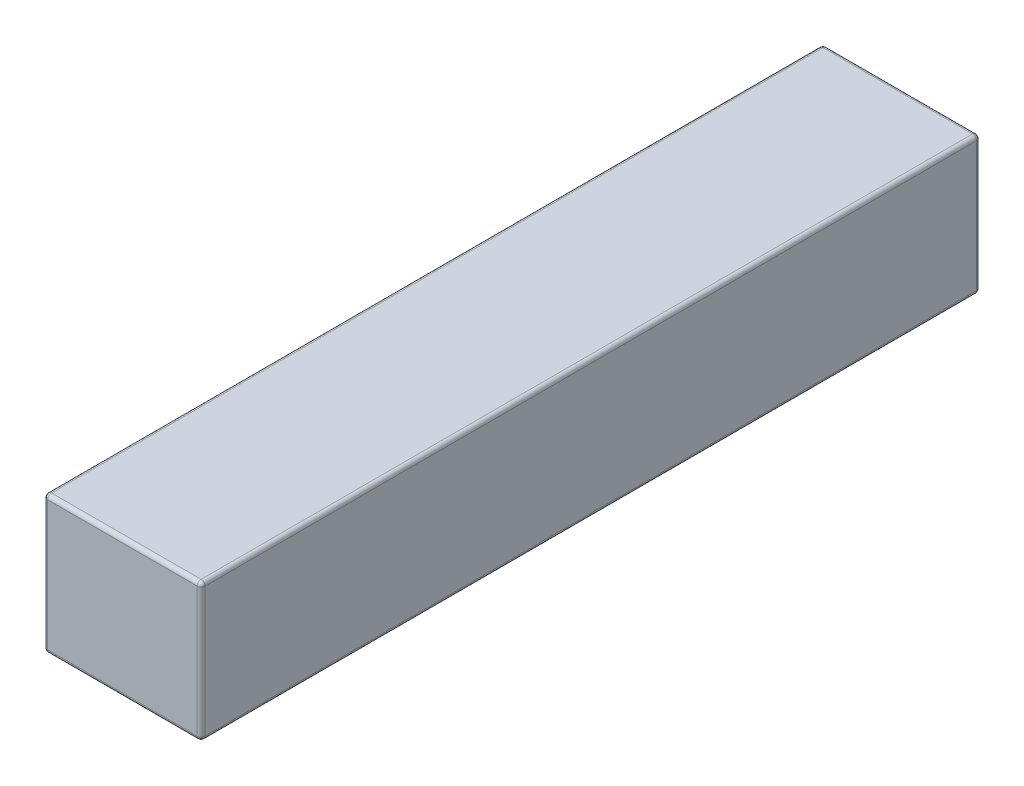
SolidWorks part; units mm, degrees
ref_plane "Front Plane" through (0, 0, 0) normal (0, 0, 1) x (1, 0, 0)
ref_plane "Top Plane" through (0, 0, 0) normal (0, 1, 0) x (1, 0, 0)
ref_plane "Right Plane" through (0, 0, 0) normal (1, 0, 0) x (0, 0, -1)
sketch "Sketch1" plane through (0, 0, 0) normal (0, 0, 1) x (1, 0, 0)
  line L1 (200, -175) -> (-200, -175)
  line L2 (200, -175) -> (200, 175)
  line L3 (200, 175) -> (-200, 175)
  line L4 (-200, -175) -> (-200, 175)
  line L5 (200, -175) -> (-200, 175) construction
  line L6 (200, 175) -> (-200, -175) construction
  point P0 (0, 0)
  dimension "D1" = 400
  dimension "D2" = 350
extrude "Boss-Extrude1" add sketch "Sketch1" along normal blind 1980
fillet "Fillet1" radius 10 12 edges at (-200, -175, 990) (200, -175, 990) (200, 175, 990) (-200, 175, 990) (0, 175, 1980) (200, 0, 1980) (0, -175, 1980) (-200, 0, 1980) (0, 175, 0) (200, 0, 0) (0, -175, 0) (-200, 0, 0)
